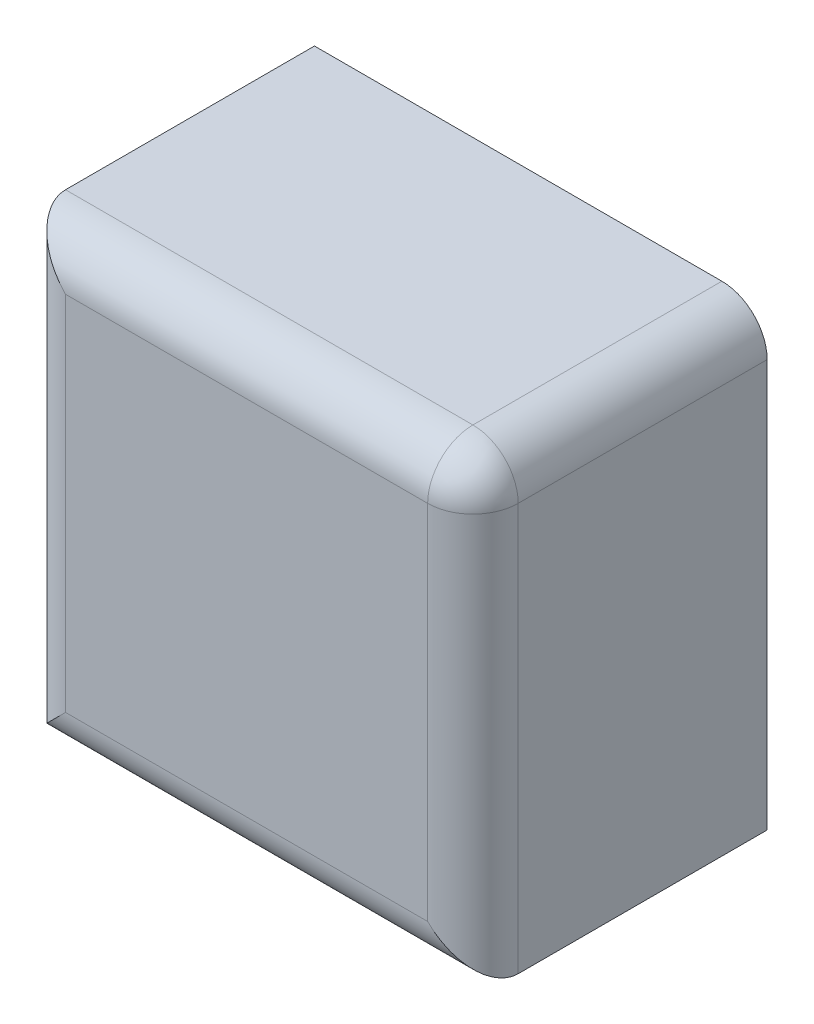
SolidWorks part; units mm, degrees
material "6061 Alloy"
ref_plane "Front Plane" through (0, 0, 0) normal (0, 0, 1) x (1, 0, 0)
ref_plane "Top Plane" through (0, 0, 0) normal (0, 1, 0) x (1, 0, 0)
ref_plane "Right Plane" through (0, 0, 0) normal (1, 0, 0) x (0, 0, -1)
sketch "Sketch1" plane through (0, 0, 0) normal (0, 0, 1) x (1, 0, 0)
  line L1 (0, 0) -> (10, 0)
  line L2 (0, 0) -> (0, 10)
  line L3 (0, 10) -> (10, 10)
  line L4 (10, 0) -> (10, 10)
  dimension "D1" = 10
extrude "Boss-Extrude1" add sketch "Sketch1" along normal blind 6.5
fillet "Fillet1" radius 1 5 edges at (5, 10, 6.5) (10, 5, 6.5) (5, 0, 6.5) (0, 5, 6.5) (10, 10, 3.25)
hole_wizard "M2 Clearance Hole1" positions "Sketch2" profile "Sketch3" hole size "M2" standard "ANSI Metric"
sketch "Sketch2" plane through (0, 0, 0) normal (0, 0, -1) x (-1, 0, 0)
  line L0 (-9, 10) -> (0, 10) construction
  line L1 (-10, 0) -> (-10, 9) construction
  point P0 (-3.5, 3.5)
  dimension "D1" = 6.5
  dimension "D2" = 6.5
sketch "Sketch3" plane through (3.5, 3.5, 0) normal (1, 0, 0) x (0, 1, 0)
  line L0 (0, 0) -> (0, 4.721)
  line L1 (0, 4.721) -> (1.2, 4)
  line L2 (1.2, 4) -> (1.2, 0)
  line L5 (1.2, 0) -> (0, 0)
  line L10 (0, 4.721) -> (-1.2, 4) construction
  line L11 (0, -6.35) -> (0, 107.95) construction
  dimension "Hole Dia." = 2.4
  dimension "Hole Depth" = 4
  dimension "Drill Angle" = 118
